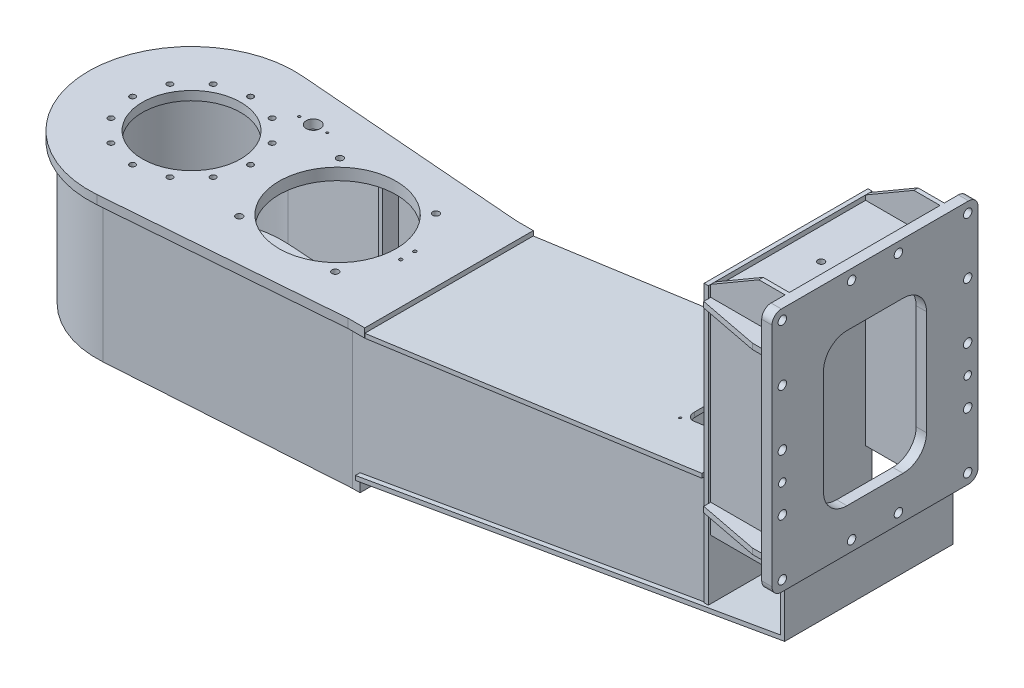
SolidWorks part; units mm, degrees
ref_plane "正面" through (0, 0, 0) normal (0, 0, 1) x (1, 0, 0)
ref_plane "平面" through (0, 0, 0) normal (0, 1, 0) x (1, 0, 0)
ref_plane "右側面" through (0, 0, 0) normal (1, 0, 0) x (0, 0, -1)
sketch "ｽｹｯﾁ1" plane through (0, 0, 0) normal (0, 1, 0) x (1, 0, 0)
  circle A0 centre (0, 0) radius 203
  circle A1 centre (0, 0) radius 194
extrude "ﾎﾞｽ - 押し出し1" add sketch "ｽｹｯﾁ1" against normal blind 301
sketch "ｽｹｯﾁ2" plane through (0, 0, 0) normal (0, 1, 0) x (1, 0, 0)
  line L0 (0, 0) -> (16.2249, -249.4729)
  line L1 (16.2249, -249.4729) -> (300, -249.4729)
  line L2 (300, -249.4729) -> (300, 249.4729)
  line L3 (300, 249.4729) -> (16.2249, 249.4729)
  line L4 (16.2249, 249.4729) -> (0, 0)
extrude "ｶｯﾄ - 押し出し1" cut sketch "ｽｹｯﾁ2" against normal through all and the other way through all
ref_plane "平面1" through (0, -301, 0) normal (0, 1, 0) x (1, 0, 0)
sketch "ｽｹｯﾁ4" plane through (0, -301, 0) normal (0, 1, 0) x (1, 0, 0)
  circle A0 centre (0, 0) radius 194
extrude "ﾎﾞｽ - 押し出し2" add sketch "ｽｹｯﾁ4" along normal blind 20
sketch "ｽｹｯﾁ5" plane through (0, -301, 0) normal (0, 1, 0) x (1, 0, 0)
  line L0 (12.5905, -193.591) -> (513.7, -161)
  line L1 (513.7, -161) -> (518, -161)
  line L2 (518, -161) -> (518, 161)
  line L3 (518, 161) -> (513.7, 161)
  line L4 (513.7, 161) -> (12.5905, 193.591)
  line L5 (12.5905, 193.591) -> (12.5905, -193.591)
extrude "ﾎﾞｽ - 押し出し3" add sketch "ｽｹｯﾁ5" along normal blind 20
sketch "ｽｹｯﾁ6" plane through (0, -301, 0) normal (0, 1, 0) x (1, 0, 0)
  circle A0 centre (0, 0) radius 159
sketch "ｽｹｯﾁ7" plane through (0, -301, 0) normal (0, 1, 0) x (1, 0, 0)
  circle A0 centre (0, 0) radius 159
extrude "ｶｯﾄ - 押し出し3" cut sketch "ｽｹｯﾁ7" along normal blind 20
sketch "ｽｹｯﾁ8" plane through (0, -301, 0) normal (0, 1, 0) x (1, 0, 0)
  line L0 (10.319, -158.6648) -> (468.0175, -128.8976)
  line L1 (468.0175, -128.8976) -> (468.0175, 128.8976)
  line L2 (468.0175, 128.8976) -> (10.319, 158.6648)
  line L3 (10.319, 158.6648) -> (10.319, -158.6648)
sketch "ｽｹｯﾁ9" plane through (0, -301, 0) normal (0, 1, 0) x (1, 0, 0)
  line L0 (10.319, -158.6648) -> (468.0175, -128.8976)
  line L1 (468.0175, -128.8976) -> (468.0175, 128.8976)
  line L2 (468.0175, 128.8976) -> (10.319, 158.6648)
  line L3 (10.319, 158.6648) -> (10.319, -158.6648)
extrude "ｶｯﾄ - 押し出し5" cut sketch "ｽｹｯﾁ9" along normal blind 20
fillet "ﾌｨﾚｯﾄ1" radius 25 2 edges at (468.0175, -291, -128.8976) (468.0175, -291, 128.8976)
sketch "ｽｹｯﾁ10" plane through (0, 0, 0) normal (0, 1, 0) x (1, 0, 0)
  line L0 (12.5905, 193.591) -> (513.7, 161)
  line L1 (513.7, 161) -> (530, 161)
  line L2 (530, 161) -> (530, 170)
  line L3 (530, 170) -> (514, 170)
  line L4 (514, 170) -> (13.1746, 202.572)
  line L5 (13.1746, 202.572) -> (12.5905, 193.591)
  line L6 (12.5905, -193.591) -> (513.7, -161)
  line L7 (513.7, -161) -> (530, -161)
  line L8 (530, -161) -> (530, -170)
  line L9 (530, -170) -> (514, -170)
  line L10 (514, -170) -> (13.1746, -202.572)
  line L11 (13.1746, -202.572) -> (12.5905, -193.591)
extrude "ﾎﾞｽ - 押し出し4" add sketch "ｽｹｯﾁ10" against normal blind 301
sketch "ｽｹｯﾁ11" plane through (0, 0, 0) normal (0, 1, 0) x (1, 0, 0)
  circle A0 centre (0, 0) radius 220
extrude "ﾎﾞｽ - 押し出し5" add sketch "ｽｹｯﾁ11" along normal blind 19
sketch "ｽｹｯﾁ12" plane through (0, 0, 0) normal (0, 1, 0) x (1, 0, 0)
  line L0 (17.3506, -219.3147) -> (514.3, -180)
  line L1 (514.3, -180) -> (550, -180)
  line L2 (550, -180) -> (550, 180)
  line L3 (550, 180) -> (514.3, 180)
  line L4 (514.3, 180) -> (17.3506, 219.3147)
  line L5 (17.3506, 219.3147) -> (17.3506, -219.3147)
extrude "ﾎﾞｽ - 押し出し6" add sketch "ｽｹｯﾁ12" along normal blind 19
sketch "ｽｹｯﾁ13" plane through (0, 0, 0) normal (0, 1, 0) x (1, 0, 0)
  line L0 (175, 135) -> (475, 135)
  line L1 (475, 135) -> (475, -135)
  line L2 (475, -135) -> (175, -135)
  line L3 (175, -135) -> (175, 135)
extrude "ﾎﾞｽ - 押し出し7" add sketch "ｽｹｯﾁ13" against normal blind 6
ref_plane "平面2" through (518, 0, 0) normal (1, 0, 0) x (0, 0, -1)
sketch "ｽｹｯﾁ15" plane through (518, 0, 0) normal (1, 0, 0) x (0, 0, -1)
  line L0 (161, -301) -> (-161, -301)
  line L1 (-161, -301) -> (-161, -7)
  line L2 (-161, -7) -> (-151, 3)
  line L3 (-151, 3) -> (151, 3)
  line L4 (151, 3) -> (161, -7)
  line L5 (161, -7) -> (161, -301)
extrude "ﾎﾞｽ - 押し出し8" add sketch "ｽｹｯﾁ15" along normal blind 12
sketch "ｽｹｯﾁ16" plane through (518, 0, 0) normal (1, 0, 0) x (0, 0, -1)
  line L0 (-111, -220) -> (-111, -97)
  line L1 (-81, -67) -> (81, -67)
  line L2 (111, -97) -> (111, -220)
  line L3 (81, -250) -> (-81, -250)
  arc A0 (-111, -97) -> (-81, -67) centre (-81, -97) cw
  arc A1 (81, -67) -> (111, -97) centre (81, -97) cw
  arc A2 (111, -220) -> (81, -250) centre (81, -220) cw
  arc A3 (-81, -250) -> (-111, -220) centre (-81, -220) cw
sketch "ｽｹｯﾁ17" plane through (518, 0, 0) normal (1, 0, 0) x (0, 0, -1)
  line L0 (-111, -220) -> (-111, -97)
  line L1 (-81, -67) -> (81, -67)
  line L2 (111, -97) -> (111, -220)
  line L3 (81, -250) -> (-81, -250)
  arc A0 (-111, -97) -> (-81, -67) centre (-81, -97) cw
  arc A1 (81, -67) -> (111, -97) centre (81, -97) cw
  arc A2 (111, -220) -> (81, -250) centre (81, -220) cw
  arc A3 (-81, -250) -> (-111, -220) centre (-81, -220) cw
extrude "ｶｯﾄ - 押し出し7" cut sketch "ｽｹｯﾁ17" along normal blind 12
ref_plane "平面3" through (0, 0, 161) normal (0, 0, 1) x (1, 0, 0)
ref_plane "平面4" through (0, 0, -161) normal (0, 0, 1) x (1, 0, 0)
sketch "ｽｹｯﾁ20" plane through (0, 0, 161) normal (0, 0, 1) x (1, 0, 0)
  line L0 (530, -273.1369) -> (1270, -143.5554)
  line L1 (1270, -143.5554) -> (1270, 109.9881)
  line L2 (1270, 109.9881) -> (530, 6.2151)
  line L3 (530, 6.2151) -> (530, -273.1369)
extrude "ﾎﾞｽ - 押し出し9" add sketch "ｽｹｯﾁ20" along normal blind 9
sketch "ｽｹｯﾁ21" plane through (0, 0, -161) normal (0, 0, 1) x (1, 0, 0)
  line L0 (530, -273.1369) -> (1270, -143.5554)
  line L1 (1270, -143.5554) -> (1270, 109.9881)
  line L2 (1270, 109.9881) -> (530, 6.2151)
  line L3 (530, 6.2151) -> (530, -273.1369)
extrude "ﾎﾞｽ - 押し出し10" add sketch "ｽｹｯﾁ21" against normal blind 9
sketch "ｽｹｯﾁ22" plane through (0, 0, 0) normal (0, 0, 1) x (1, 0, 0)
  line L0 (551.2, 0.1) -> (1270, 100.9)
  line L1 (1270, 100.9) -> (1270, 109.9881)
  line L2 (1270, 109.9881) -> (549.9501, 9.0128)
  line L3 (549.9501, 9.0128) -> (551.2, 0.1)
extrude "ﾎﾞｽ - 押し出し11" add sketch "ｽｹｯﾁ22" against normal blind 180 and the other way blind 180
sketch "ｽｹｯﾁ23" plane through (0, 0, 0) normal (0, 0, 1) x (1, 0, 0)
  line L0 (530, -264) -> (1438, -105)
  line L1 (1438, -105) -> (1438, -5)
  line L2 (1438, -5) -> (1447, -5)
  line L3 (1447, -5) -> (1447, -112.561)
  line L4 (1447, -112.561) -> (530, -273.1369)
  line L5 (530, -273.1369) -> (530, -264)
extrude "ﾎﾞｽ - 押し出し12" add sketch "ｽｹｯﾁ23" against normal blind 180 and the other way blind 180
sketch "ｽｹｯﾁ24" plane through (0, 0, 0) normal (0, 0, 1) x (1, 0, 0)
  line L0 (909.0501, 59.3707) -> (917.9629, 60.6206)
  line L1 (917.9629, 60.6206) -> (954.3466, -198.8296)
  line L2 (954.3466, -198.8296) -> (945.4763, -200.3828)
  line L3 (945.4763, -200.3828) -> (909.0501, 59.3707)
extrude "ﾎﾞｽ - 押し出し13" add sketch "ｽｹｯﾁ24" against normal blind 161 and the other way blind 161
ref_plane "平面5" through (0, 0, 161) normal (0, 0, 1) x (1, 0, 0)
ref_plane "平面6" through (0, 0, -161) normal (0, 0, 1) x (1, 0, 0)
sketch "ｽｹｯﾁ29" plane through (908.596, 127.4158, 0) normal (0.9903, 0.1389, 0) x (0, 0, -1)
  line L0 (81, -270.0172) -> (-81, -270.0172)
  line L1 (-111, -240.0172) -> (-111, -157.0172)
  line L2 (-81, -127.0172) -> (81, -127.0172)
  line L3 (111, -157.0172) -> (111, -240.0172)
  arc A0 (-81, -270.0172) -> (-111, -240.0172) centre (-81, -240.0172) cw
  arc A1 (-111, -157.0172) -> (-81, -127.0172) centre (-81, -157.0172) cw
  arc A2 (81, -127.0172) -> (111, -157.0172) centre (81, -157.0172) cw
  arc A3 (111, -240.0172) -> (81, -270.0172) centre (81, -240.0172) cw
extrude "ｶｯﾄ - 押し出し8" cut sketch "ｽｹｯﾁ29" against normal blind 9
ref_plane "平面7" through (1270, 0, 0) normal (1, 0, 0) x (0, 0, -1)
sketch "ｽｹｯﾁ31" plane through (1270, 0, 0) normal (1, 0, 0) x (0, 0, -1)
  line L0 (175, -132) -> (-175, -132)
  line L1 (-175, -132) -> (-175, 459)
  line L2 (-175, 459) -> (175, 459)
  line L3 (175, 459) -> (175, -132)
extrude "ﾎﾞｽ - 押し出し14" add sketch "ｽｹｯﾁ31" along normal blind 9
sketch "ｽｹｯﾁ32" plane through (0, 0, 161) normal (0, 0, 1) x (1, 0, 0)
  line L0 (1279, -5) -> (1438, -5)
  line L1 (1438, -5) -> (1438, 519)
  line L2 (1438, 519) -> (1382, 519)
  line L3 (1382, 519) -> (1279, 459)
  line L4 (1279, 459) -> (1279, -5)
ref_plane "平面8" through (0, 0, 161) normal (0, 0, 1) x (1, 0, 0)
ref_plane "平面9" through (0, 0, -161) normal (0, 0, 1) x (1, 0, 0)
ref_plane "平面10" through (1270, 0, 0) normal (1, 0, 0) x (0, 0, -1)
sketch "ｽｹｯﾁ36" plane through (0, 0, 161) normal (0, 0, 1) x (1, 0, 0)
  line L0 (1279, -5) -> (1460, -5)
  line L1 (1460, -5) -> (1460, 519)
  line L2 (1460, 519) -> (1382, 519)
  line L3 (1382, 519) -> (1279, 459)
  line L4 (1279, 459) -> (1279, -5)
extrude "ﾎﾞｽ - 押し出し16" add sketch "ｽｹｯﾁ36" along normal blind 9
sketch "ｽｹｯﾁ37" plane through (0, 0, -161) normal (0, 0, 1) x (1, 0, 0)
  line L0 (1279, -5) -> (1460, -5)
  line L1 (1460, -5) -> (1460, 519)
  line L2 (1460, 519) -> (1382, 519)
  line L3 (1382, 519) -> (1279, 459)
  line L4 (1279, 459) -> (1279, -5)
extrude "ﾎﾞｽ - 押し出し17" add sketch "ｽｹｯﾁ37" against normal blind 9
ref_plane "平面11" through (0, 44, 0) normal (0, 1, 0) x (1, 0, 0)
sketch "ｽｹｯﾁ39" plane through (0, 44, 0) normal (0, 1, 0) x (1, 0, 0)
  line L0 (1279, 170) -> (1431, 170)
  line L1 (1431, 170) -> (1438, 177)
  line L2 (1438, 177) -> (1438, 203)
  line L3 (1438, 203) -> (1431, 210)
  line L4 (1431, 210) -> (1408, 210)
  line L5 (1408, 210) -> (1279, 185)
  line L6 (1279, 185) -> (1279, 170)
  line L7 (1279, -170) -> (1431, -170)
  line L8 (1431, -170) -> (1438, -177)
  line L9 (1438, -177) -> (1438, -203)
  line L10 (1438, -203) -> (1431, -210)
  line L11 (1431, -210) -> (1408, -210)
  line L12 (1408, -210) -> (1279, -185)
  line L13 (1279, -185) -> (1279, -170)
extrude "ﾎﾞｽ - 押し出し18" add sketch "ｽｹｯﾁ39" along normal blind 12
ref_plane "平面12" through (0, 423, 0) normal (0, 1, 0) x (1, 0, 0)
sketch "ｽｹｯﾁ41" plane through (0, 423, 0) normal (0, 1, 0) x (1, 0, 0)
  line L0 (1279, 170) -> (1431, 170)
  line L1 (1431, 170) -> (1438, 177)
  line L2 (1438, 177) -> (1438, 203)
  line L3 (1438, 203) -> (1431, 210)
  line L4 (1431, 210) -> (1408, 210)
  line L5 (1408, 210) -> (1279, 185)
  line L6 (1279, 185) -> (1279, 170)
  line L7 (1279, -170) -> (1431, -170)
  line L8 (1431, -170) -> (1438, -177)
  line L9 (1438, -177) -> (1438, -203)
  line L10 (1438, -203) -> (1431, -210)
  line L11 (1431, -210) -> (1408, -210)
  line L12 (1408, -210) -> (1279, -185)
  line L13 (1279, -185) -> (1279, -170)
extrude "ﾎﾞｽ - 押し出し19" add sketch "ｽｹｯﾁ41" along normal blind 12
ref_plane "平面13" through (0, 437, 0) normal (0, 1, 0) x (1, 0, 0)
sketch "ｽｹｯﾁ43" plane through (0, 437, 0) normal (0, 1, 0) x (1, 0, 0)
  line L0 (1279, 161) -> (1438, 161)
  line L1 (1438, 161) -> (1438, -161)
  line L2 (1438, -161) -> (1279, -161)
  line L3 (1279, -161) -> (1279, 161)
extrude "ﾎﾞｽ - 押し出し20" add sketch "ｽｹｯﾁ43" along normal blind 12
ref_plane "平面14" through (1438, 0, 0) normal (1, 0, 0) x (0, 0, -1)
sketch "ｽｹｯﾁ45" plane through (1438, 0, 0) normal (1, 0, 0) x (0, 0, -1)
  line L0 (-220, 15) -> (-220, 499)
  line L1 (-200, 519) -> (200, 519)
  line L2 (220, 499) -> (220, 15)
  line L3 (200, -5) -> (-200, -5)
  arc A0 (-220, 499) -> (-200, 519) centre (-200, 499) cw
  arc A1 (200, 519) -> (220, 499) centre (200, 499) cw
  arc A2 (220, 15) -> (200, -5) centre (200, 15) cw
  arc A3 (-200, -5) -> (-220, 15) centre (-200, 15) cw
extrude "ﾎﾞｽ - 押し出し21" add sketch "ｽｹｯﾁ45" along normal blind 22
sketch "ｽｹｯﾁ46" plane through (1438, 0, 0) normal (1, 0, 0) x (0, 0, -1)
  line L0 (-110, 135) -> (-110, 359)
  line L1 (-60, 409) -> (60, 409)
  line L2 (110, 359) -> (110, 135)
  line L3 (60, 85) -> (-60, 85)
  arc A0 (-110, 359) -> (-60, 409) centre (-60, 359) cw
  arc A1 (60, 409) -> (110, 359) centre (60, 359) cw
  arc A2 (110, 135) -> (60, 85) centre (60, 135) cw
  arc A3 (-60, 85) -> (-110, 135) centre (-60, 135) cw
sketch "ｽｹｯﾁ47" plane through (1438, 0, 0) normal (1, 0, 0) x (0, 0, -1)
  line L0 (-110, 135) -> (-110, 359)
  line L1 (-60, 409) -> (60, 409)
  line L2 (110, 359) -> (110, 135)
  line L3 (60, 85) -> (-60, 85)
  arc A0 (-110, 359) -> (-60, 409) centre (-60, 359) cw
  arc A1 (60, 409) -> (110, 359) centre (60, 359) cw
  arc A2 (110, 135) -> (60, 85) centre (60, 135) cw
  arc A3 (-60, 85) -> (-110, 135) centre (-60, 135) cw
extrude "ｶｯﾄ - 押し出し10" cut sketch "ｽｹｯﾁ47" along normal blind 22
sketch "ｽｹｯﾁ48" plane through (0, 0, 0) normal (0, 1, 0) x (1, 0, 0)
  line L0 (253.6175, 145.9656) -> (262.6175, 145.3656)
  line L1 (262.6175, 145.3656) -> (264.7175, 177.1935)
  line L2 (264.7175, 177.1935) -> (255.7175, 177.7788)
  line L3 (255.7175, 177.7788) -> (253.6175, 145.9656)
  line L4 (253.6175, -145.9656) -> (262.6175, -145.3656)
  line L5 (262.6175, -145.3656) -> (264.7175, -177.1935)
  line L6 (264.7175, -177.1935) -> (255.7175, -177.7788)
  line L7 (255.7175, -177.7788) -> (253.6175, -145.9656)
extrude "ﾎﾞｽ - 押し出し22" add sketch "ｽｹｯﾁ48" against normal blind 301
sketch "ｽｹｯﾁ49" plane through (0, 0, 0) normal (0, 1, 0) x (1, 0, 0)
  circle A0 centre (0, 0) radius 105
sketch "ｽｹｯﾁ50" plane through (0, 0, 0) normal (0, 1, 0) x (1, 0, 0)
  circle A0 centre (0, 0) radius 105
extrude "ｶｯﾄ - 押し出し12" cut sketch "ｽｹｯﾁ50" along normal blind 19
sketch "ｽｹｯﾁ51" plane through (0, 0, 0) normal (0, 1, 0) x (1, 0, 0)
  circle A0 centre (126, 0) radius 6
  circle A1 centre (109.1192, -63) radius 6
  circle A2 centre (63, -109.1192) radius 6
  circle A3 centre (0, -126) radius 6
  circle A4 centre (-63, -109.1192) radius 6
  circle A5 centre (-109.1192, -63) radius 6
  circle A6 centre (-126, 0) radius 6
  circle A7 centre (-109.1192, 63) radius 6
  circle A8 centre (-63, 109.1192) radius 6
  circle A9 centre (0, 126) radius 6
  circle A10 centre (63, 109.1192) radius 6
  circle A11 centre (109.1192, 63) radius 6
sketch "ｽｹｯﾁ52" plane through (0, 0, 0) normal (0, 1, 0) x (1, 0, 0)
  circle A0 centre (126, 0) radius 6
  circle A1 centre (109.1192, -63) radius 6
  circle A2 centre (63, -109.1192) radius 6
  circle A3 centre (0, -126) radius 6
  circle A4 centre (-63, -109.1192) radius 6
  circle A5 centre (-109.1192, -63) radius 6
  circle A6 centre (-126, 0) radius 6
  circle A7 centre (-109.1192, 63) radius 6
  circle A8 centre (-63, 109.1192) radius 6
  circle A9 centre (0, 126) radius 6
  circle A10 centre (63, 109.1192) radius 6
  circle A11 centre (109.1192, 63) radius 6
extrude "ｶｯﾄ - 押し出し14" cut sketch "ｽｹｯﾁ52" along normal blind 19
sketch "ｽｹｯﾁ53" plane through (0, 0, 0) normal (0, 1, 0) x (1, 0, 0)
  circle A0 centre (119, 141) radius 15
sketch "ｽｹｯﾁ54" plane through (0, 0, 0) normal (0, 1, 0) x (1, 0, 0)
  circle A0 centre (119, 141) radius 15
extrude "ｶｯﾄ - 押し出し16" cut sketch "ｽｹｯﾁ54" along normal blind 19
sketch "ｽｹｯﾁ55" plane through (0, 0, 0) normal (0, 1, 0) x (1, 0, 0)
  circle A0 centre (89, 141) radius 2.5
  circle A1 centre (149, 141) radius 2.5
sketch "ｽｹｯﾁ56" plane through (0, 0, 0) normal (0, 1, 0) x (1, 0, 0)
  circle A0 centre (89, 141) radius 2.5
  circle A1 centre (149, 141) radius 2.5
extrude "ｶｯﾄ - 押し出し18" cut sketch "ｽｹｯﾁ56" along normal blind 19
ref_plane "平面15" through (0, -6, 0) normal (0, 1, 0) x (1, 0, 0)
sketch "ｽｹｯﾁ58" plane through (0, -6, 0) normal (0, 1, 0) x (1, 0, 0)
  circle A0 centre (312, 0) radius 125
sketch "ｽｹｯﾁ59" plane through (0, -6, 0) normal (0, 1, 0) x (1, 0, 0)
  circle A0 centre (312, 0) radius 125
extrude "ｶｯﾄ - 押し出し20" cut sketch "ｽｹｯﾁ59" along normal blind 25
sketch "ｽｹｯﾁ60" plane through (0, -6, 0) normal (0, 1, 0) x (1, 0, 0)
  circle A0 centre (209.5, 107.5) radius 7
  circle A1 centre (209.5, -107.5) radius 7
  circle A2 centre (414.5, 107.5) radius 7
  circle A3 centre (414.5, -107.5) radius 7
sketch "ｽｹｯﾁ61" plane through (0, -6, 0) normal (0, 1, 0) x (1, 0, 0)
  circle A0 centre (209.5, 107.5) radius 7
  circle A1 centre (209.5, -107.5) radius 7
  circle A2 centre (414.5, 107.5) radius 7
  circle A3 centre (414.5, -107.5) radius 7
extrude "ｶｯﾄ - 押し出し22" cut sketch "ｽｹｯﾁ61" along normal blind 25
sketch "ｽｹｯﾁ62" plane through (0, -6, 0) normal (0, 1, 0) x (1, 0, 0)
  circle A0 centre (462, 15) radius 3.4
  circle A1 centre (462, -15) radius 3.4
sketch "ｽｹｯﾁ63" plane through (0, -6, 0) normal (0, 1, 0) x (1, 0, 0)
  circle A0 centre (462, 15) radius 3.4
  circle A1 centre (462, -15) radius 3.4
extrude "ｶｯﾄ - 押し出し24" cut sketch "ｽｹｯﾁ63" along normal blind 25
sketch "ｽｹｯﾁ64" plane through (9.3669, -66.7952, 0) normal (-0.1389, 0.9903, 0) x (0.9903, 0.1389, 0)
  line L0 (1205.5769, 55) -> (1205.5769, -55)
  line L1 (1185.5769, -75) -> (1150.5769, -75)
  line L2 (1130.5769, -55) -> (1130.5769, 55)
  line L3 (1150.5769, 75) -> (1185.5769, 75)
  arc A0 (1205.5769, -55) -> (1185.5769, -75) centre (1185.5769, -55) cw
  arc A1 (1150.5769, -75) -> (1130.5769, -55) centre (1150.5769, -55) cw
  arc A2 (1130.5769, 55) -> (1150.5769, 75) centre (1150.5769, 55) cw
  arc A3 (1185.5769, 75) -> (1205.5769, 55) centre (1185.5769, 55) cw
extrude "ｶｯﾄ - 押し出し25" cut sketch "ｽｹｯﾁ64" against normal blind 9
sketch "ｽｹｯﾁ65" plane through (9.3669, -66.7952, 0) normal (-0.1389, 0.9903, 0) x (0.9903, 0.1389, 0)
  circle A0 centre (1125.5769, 80) radius 2.5
  circle A1 centre (1125.5769, -80) radius 2.5
  circle A2 centre (1210.5769, 80) radius 2.5
  circle A3 centre (1210.5769, -80) radius 2.5
extrude "ｶｯﾄ - 押し出し26" cut sketch "ｽｹｯﾁ65" against normal blind 9
sketch "ｽｹｯﾁ66" plane through (1270, 0, 0) normal (1, 0, 0) x (0, 0, -1)
  circle A0 centre (0, 319) radius 65
sketch "ｽｹｯﾁ67" plane through (1270, 0, 0) normal (1, 0, 0) x (0, 0, -1)
  circle A0 centre (0, 319) radius 65
extrude "ｶｯﾄ - 押し出し28" cut sketch "ｽｹｯﾁ67" along normal blind 9
sketch "ｽｹｯﾁ68" plane through (1270, 0, 0) normal (1, 0, 0) x (0, 0, -1)
  circle A0 centre (-53.033, 372.033) radius 2.5
  circle A1 centre (53.033, 372.033) radius 2.5
  circle A2 centre (53.033, 265.967) radius 2.5
  circle A3 centre (-53.033, 265.967) radius 2.5
sketch "ｽｹｯﾁ69" plane through (1270, 0, 0) normal (1, 0, 0) x (0, 0, -1)
  circle A0 centre (-53.033, 372.033) radius 2.5
  circle A1 centre (53.033, 372.033) radius 2.5
  circle A2 centre (53.033, 265.967) radius 2.5
  circle A3 centre (-53.033, 265.967) radius 2.5
extrude "ｶｯﾄ - 押し出し30" cut sketch "ｽｹｯﾁ69" along normal blind 9
sketch "ｽｹｯﾁ70" plane through (0, 437, 0) normal (0, 1, 0) x (1, 0, 0)
  circle A0 centre (1345, 0) radius 7
sketch "ｽｹｯﾁ71" plane through (0, 437, 0) normal (0, 1, 0) x (1, 0, 0)
  circle A0 centre (1345, 0) radius 7
extrude "ｶｯﾄ - 押し出し32" cut sketch "ｽｹｯﾁ71" along normal blind 12
sketch "ｽｹｯﾁ72" plane through (1438, 0, 0) normal (1, 0, 0) x (0, 0, -1)
  circle A0 centre (198, 17) radius 9
  circle A1 centre (198, 137) radius 9
  circle A2 centre (198, 257) radius 9
  circle A3 centre (198, 377) radius 9
  circle A4 centre (198, 497) radius 9
  circle A5 centre (-198, 17) radius 9
  circle A6 centre (-198, 137) radius 9
  circle A7 centre (-198, 257) radius 9
  circle A8 centre (-198, 377) radius 9
  circle A9 centre (-198, 497) radius 9
  circle A10 centre (50, 17) radius 9
  circle A11 centre (50, 497) radius 9
  circle A12 centre (-50, 17) radius 9
  circle A13 centre (-50, 497) radius 9
sketch "ｽｹｯﾁ73" plane through (1438, 0, 0) normal (1, 0, 0) x (0, 0, -1)
  circle A0 centre (198, 17) radius 9
  circle A1 centre (198, 137) radius 9
  circle A2 centre (198, 257) radius 9
  circle A3 centre (198, 377) radius 9
  circle A4 centre (198, 497) radius 9
  circle A5 centre (-198, 17) radius 9
  circle A6 centre (-198, 137) radius 9
  circle A7 centre (-198, 257) radius 9
  circle A8 centre (-198, 377) radius 9
  circle A9 centre (-198, 497) radius 9
  circle A10 centre (50, 17) radius 9
  circle A11 centre (50, 497) radius 9
  circle A12 centre (-50, 17) radius 9
  circle A13 centre (-50, 497) radius 9
extrude "ｶｯﾄ - 押し出し34" cut sketch "ｽｹｯﾁ73" along normal blind 22
sketch "ｽｹｯﾁ74" plane through (1438, 0, 0) normal (1, 0, 0) x (0, 0, -1)
  circle A0 centre (198, 197) radius 8
  circle A1 centre (-198, 197) radius 8
sketch "ｽｹｯﾁ75" plane through (1438, 0, 0) normal (1, 0, 0) x (0, 0, -1)
  circle A0 centre (198, 197) radius 8
  circle A1 centre (-198, 197) radius 8
extrude "ｶｯﾄ - 押し出し36" cut sketch "ｽｹｯﾁ75" along normal blind 22
